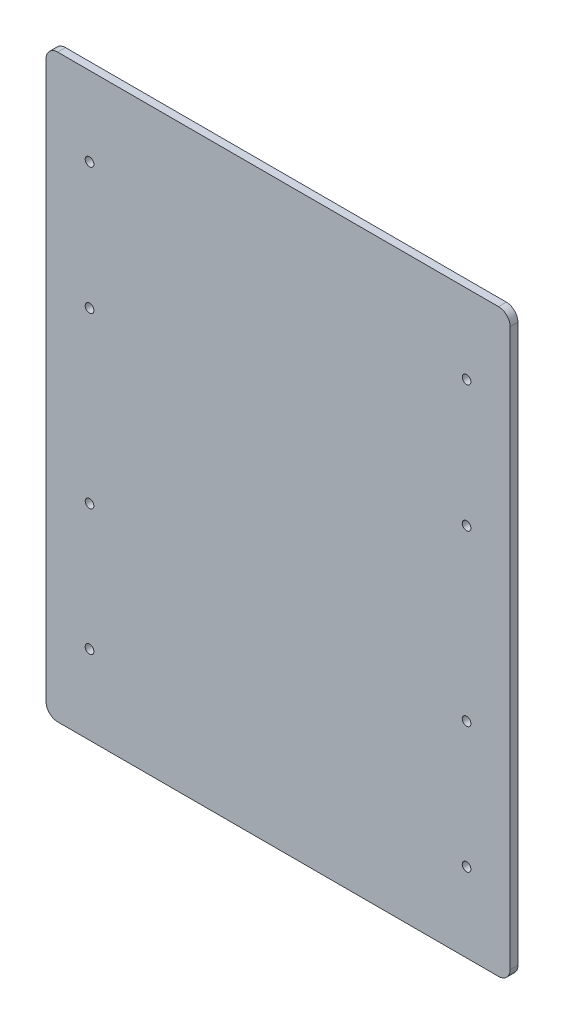
SolidWorks part; units mm, degrees
other "DetailItem1"
ref_plane "Front Plane" through (0, 0, 0) normal (0, 0, 1) x (1, 0, 0)
ref_plane "Top Plane" through (0, 0, 0) normal (0, 1, 0) x (1, 0, 0)
ref_plane "Right Plane" through (0, 0, 0) normal (1, 0, 0) x (0, 0, -1)
sketch "Sketch1" plane through (0, 0, 0) normal (0, 0, 1) x (1, 0, 0)
  line L0 (0, 196) -> (152, 196)
  line L1 (-4, 192) -> (-4, 0)
  line L2 (0, -4) -> (152, -4)
  line L3 (156, 192) -> (156, 0)
  line L4 (11, 11) -> (11, 181) construction
  line L5 (11, 181) -> (141, 181) construction
  line L6 (141, 181) -> (141, 11) construction
  line L7 (141, 11) -> (11, 11) construction
  line L8 (11, 26) -> (141, 26) construction
  line L11 (-4.009, 165.9918) -> (155.991, 165.9918) construction
  line L12 (-4.009, 127.9918) -> (155.991, 127.9918) construction
  line L14 (-4.009, 63.9918) -> (155.991, 63.9918) construction
  line L15 (155.991, 95.9918) -> (-4.009, 95.9918) construction
  arc A0 (-4, 0) -> (0, -4) centre (0, 0) ccw
  arc A1 (152, -4) -> (156, 0) centre (152, 0) ccw
  arc A2 (152, 196) -> (156, 192) centre (152, 192) cw
  arc A3 (0, 196) -> (-4, 192) centre (0, 192) ccw
  circle A4 centre (11, 11) radius 9.6889
  circle A5 centre (141, 11) radius 9.6889
  circle A6 centre (141, 181) radius 9.6889
  circle A7 centre (11, 181) radius 9.6889
  circle A8 centre (10.991, 23.2396) radius 1.495
  circle A9 centre (140.991, 23.2396) radius 1.495
  circle A10 centre (140.991, 168.744) radius 1.495
  circle A11 centre (10.991, 168.744) radius 1.495
  circle A12 centre (10.991, 125.0715) radius 1.495
  circle A13 centre (10.991, 66.7085) radius 1.495
  circle A14 centre (140.991, 66.7085) radius 1.495
  circle A15 centre (140.991, 125.0715) radius 1.495
  point P23 (0, 0)
  dimension "D1" = 4
  dimension "D2" = 15
  dimension "D3" = 15
  dimension "D4" = 15
  dimension "D5" = 15
  dimension "D6" = 15
  dimension "D7" = 15
  dimension "D8" = 15
  dimension "D9" = 15
  dimension "D10" = 15
  dimension "D11" = 38
extrude "Boss-Extrude1" add sketch "Sketch1" along normal blind 2.7 contours A7 | L0 A3 L1 A0 L2 A1 L3 A2 A14 A13 A12 A9 A8 A5 A4 A6 A7 A10 A11 A15 | A6 | A5 | A4
